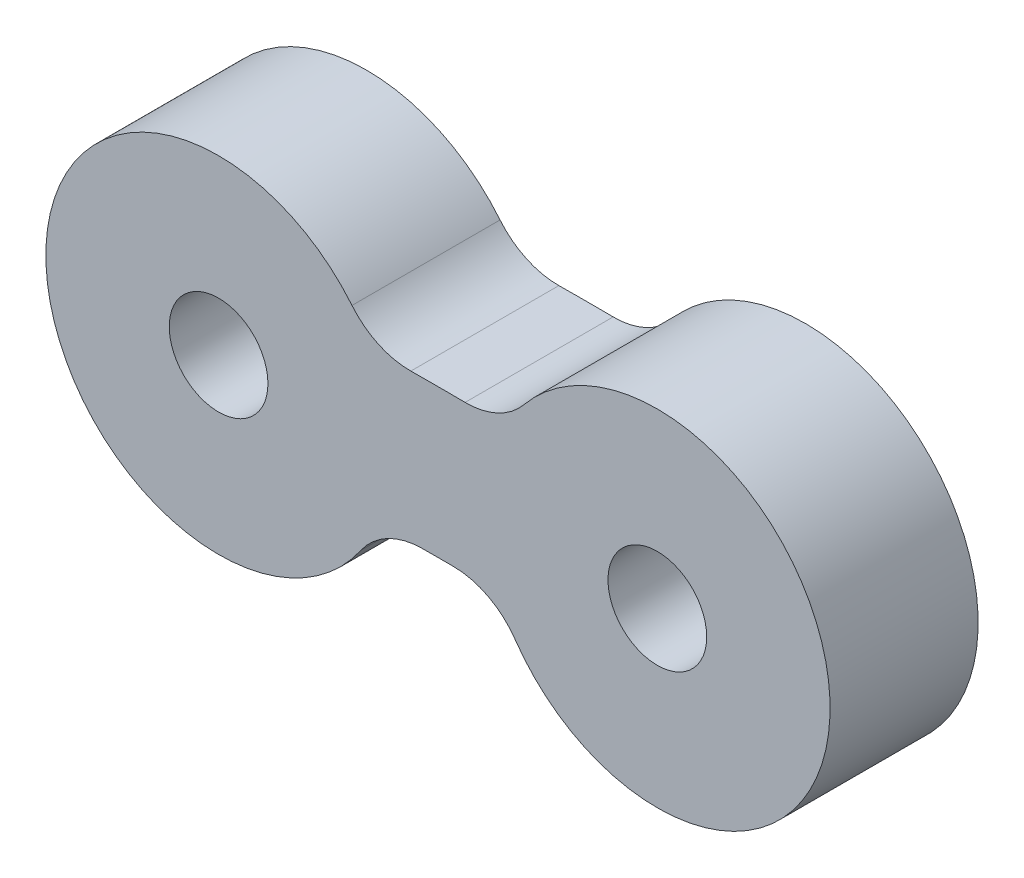
SolidWorks part; units mm, degrees
material "Acrylic (Medium-high impact)"
ref_plane "Front Plane" through (0, 0, 0) normal (0, 0, 1) x (1, 0, 0)
ref_plane "Top Plane" through (0, 0, 0) normal (0, 1, 0) x (1, 0, 0)
ref_plane "Right Plane" through (0, 0, 0) normal (1, 0, 0) x (0, 0, -1)
sketch "스케치1" plane through (0, 0, 0) normal (0, 0, 1) x (1, 0, 0)
  line L0 (1.3602, -0.0164) -> (0.9492, -1.498) construction
  line L1 (0.9492, -1.498) -> (1.2129, -3.0128) construction
  line L2 (0.7801, -10.0464) -> (0, -9.9583) construction
  line L3 (0, -9.9583) -> (-0.7801, -10.0464) construction
  line L4 (0, -9.9583) -> (0, 0) construction
  line L5 (1.3602, -0.0164) -> (-1.3602, -0.0164) construction
  line L6 (1.3602, -0.0164) -> (1.2129, -3.0128) construction
  line L7 (1.3602, -0.0164) -> (-55.7208, 2.7902) construction
  line L8 (1.2129, -3.0128) -> (-55.8682, -0.2062) construction
  line L9 (-55.7208, 2.7902) -> (-55.8682, -0.2062) construction
  line L10 (-9.4991, -2.4861) -> (-55.8682, -0.2062) construction
  arc A0 (-1.3602, -0.0164) -> (1.3602, -0.0164) centre (0, -56.4382) cw construction
  arc A1 (-1.2129, -3.0128) -> (1.2129, -3.0128) centre (0, -56.4382) cw construction
  circle A2 centre (-4.445, -1.6699) radius 3.5 construction
  circle A3 centre (4.445, -1.6699) radius 3.5 construction
  arc A4 (-4.445, -1.6699) -> (4.445, -1.6699) centre (0, -56.4382) cw construction
  circle A5 centre (-4.445, -1.6699) radius 1
  circle A6 centre (4.445, -1.6699) radius 1
  circle A7 centre (0, -13.4583) radius 3.5 construction
  circle A8 centre (0, -13.4583) radius 1
  arc A9 (0.7801, -10.0464) -> (1.6848, -3.0256) centre (1.5727, -6.5798) cw construction
  arc A10 (-1.6848, -3.0256) -> (-0.7801, -10.0464) centre (-1.5727, -6.5798) cw construction
  arc A13 (1.3602, -0.0164) -> (1.2129, -3.0128) centre (4.445, -1.6699) cw
  arc A14 (0.7801, -10.0464) -> (-0.7801, -10.0464) centre (0, -13.4583) cw construction
  arc A15 (-1.2129, -3.0128) -> (-1.3602, -0.0164) centre (-4.445, -1.6699) cw
  arc A16 (-7.3016, -3.6921) -> (-9.4991, -2.4861) centre (-9.6398, -5.3474) ccw construction
  arc A17 (-1.3602, -0.0164) -> (1.3602, -0.0164) centre (0, -56.4382) cw
  arc A19 (-1.2129, -3.0128) -> (1.2129, -3.0128) centre (0, -56.4382) cw
  dimension "D1" = 2.5
  dimension "D2" = 2
  dimension "D4" = 3.556
  dimension "D7" = 57.15
  dimension "D5" = 8.89
  dimension "D6" = 3
extrude "보스-돌출1" add sketch "스케치1" along normal blind 3
fillet "필렛1" radius 1.524 4 edges at (1.2129, -3.0128, 1.5) (-1.2129, -3.0128, 1.5) (1.3602, -0.0164, 1.5) (-1.3602, -0.0164, 1.5)
